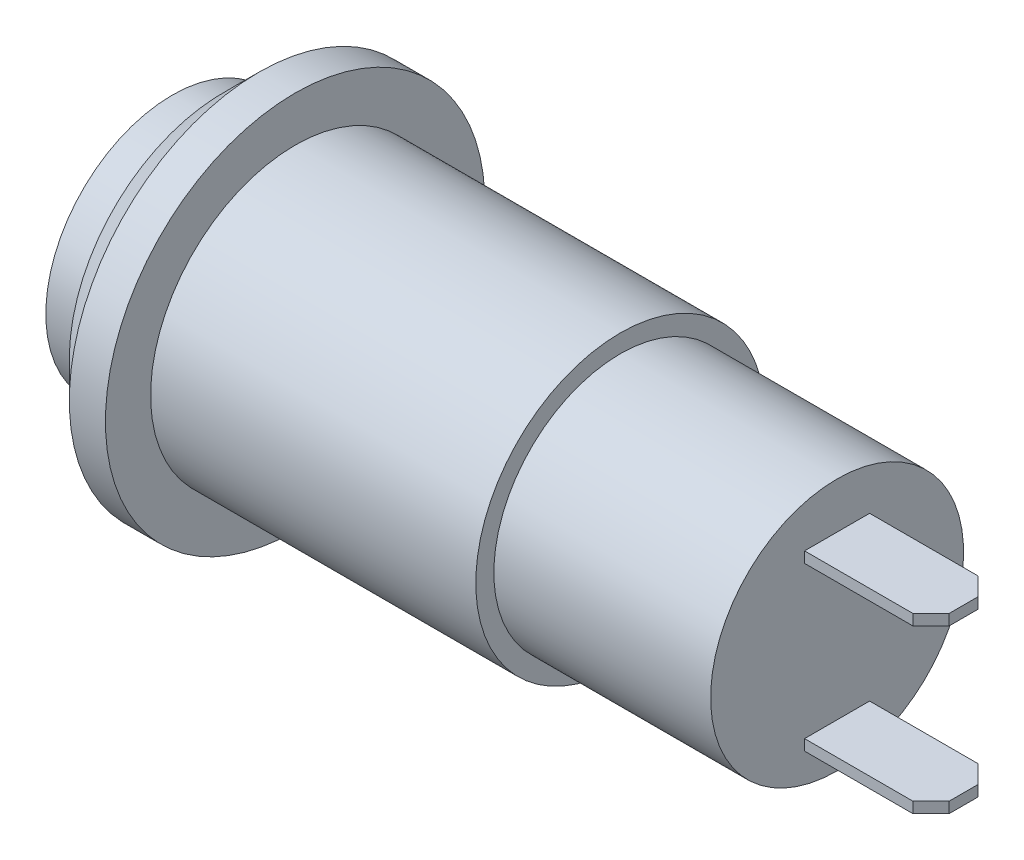
SolidWorks part; units mm, degrees
ref_plane "前视基准面" through (0, 0, 0) normal (0, 0, 1) x (1, 0, 0)
ref_plane "上视基准面" through (0, 0, 0) normal (0, 1, 0) x (1, 0, 0)
ref_plane "右视基准面" through (0, 0, 0) normal (1, 0, 0) x (0, 0, -1)
other "Configuration Table"
sketch "草图1" plane through (0, 0, 0) normal (0, 0, 1) x (1, 0, 0)
  line L0 (0, 0) -> (0, 3.5)
  line L1 (0, 3.5) -> (1.4, 3.5)
  line L2 (1.4, 3.5) -> (1.4, 5.25)
  line L4 (1.4, 5.25) -> (3.4, 5.25)
  line L5 (3.4, 5.25) -> (3.4, 4)
  line L6 (3.4, 4) -> (12.4, 4)
  line L7 (12.4, 4) -> (12.4, 3.5)
  line L8 (12.4, 3.5) -> (18.4, 3.5)
  line L9 (18.4, 3.5) -> (18.4, 0)
  line L10 (18.4, 0) -> (0, 0) construction
  line L11 (0, 0) -> (18.4, 0)
  point P3 (0, 0)
  point P13 (1.4, 5.25)
  point P14 (1.4, 4.9795)
  dimension "D1" = 7
  dimension "D2" = 10.5
  dimension "D3" = 7
  dimension "D4" = 2
  dimension "D5" = 1.4
  dimension "D6" = 8
  dimension "D7" = 9
  dimension "D8" = 18.4
revolve "旋转1" add sketch "草图1" angle 360 about L10
cosmetic thread "装饰螺纹线1" parameters "D1"=5, "D2"=6.647
chamfer "倒角1" distance 1 angle 45 1 edges at (1.4, 5.25, 0)
sketch "草图2" plane through (18.4, 0, 0) normal (1, 0, 0) x (0, 0, -1)
  line L0 (0, -2.2749) -> (0, 2.2749) construction
  line L1 (-0.9, 2.2251) -> (0.9, 2.2251)
  line L2 (-0.9, 2.2251) -> (-0.9, 1.9251)
  line L3 (-0.9, 1.9251) -> (0.9, 1.9251)
  line L4 (0.9, 2.2251) -> (0.9, 1.9251)
  line L5 (-0.9, -2.2749) -> (0.9, -2.2749)
  line L6 (-0.9, -2.2749) -> (-0.9, -2.5749)
  line L7 (-0.9, -2.5749) -> (0.9, -2.5749)
  line L8 (0.9, -2.2749) -> (0.9, -2.5749)
  point P8 (-0.9, 2.0751)
  point P11 (0, 0)
  point P12 (0, 0)
  point P13 (0, 0)
  dimension "D1" = 0.3
  dimension "D2" = 1.8
  dimension "D3" = 1.8
  dimension "D4" = 4.8
extrude "凸台-拉伸1" add sketch "草图2" along normal blind 3.5
chamfer "倒角2" distance 0.5 angle 45 4 edges at (21.9, -2.4249, -0.9) (21.9, -2.4249, 0.9) (21.9, 2.0751, -0.9) (21.9, 2.0751, 0.9)
